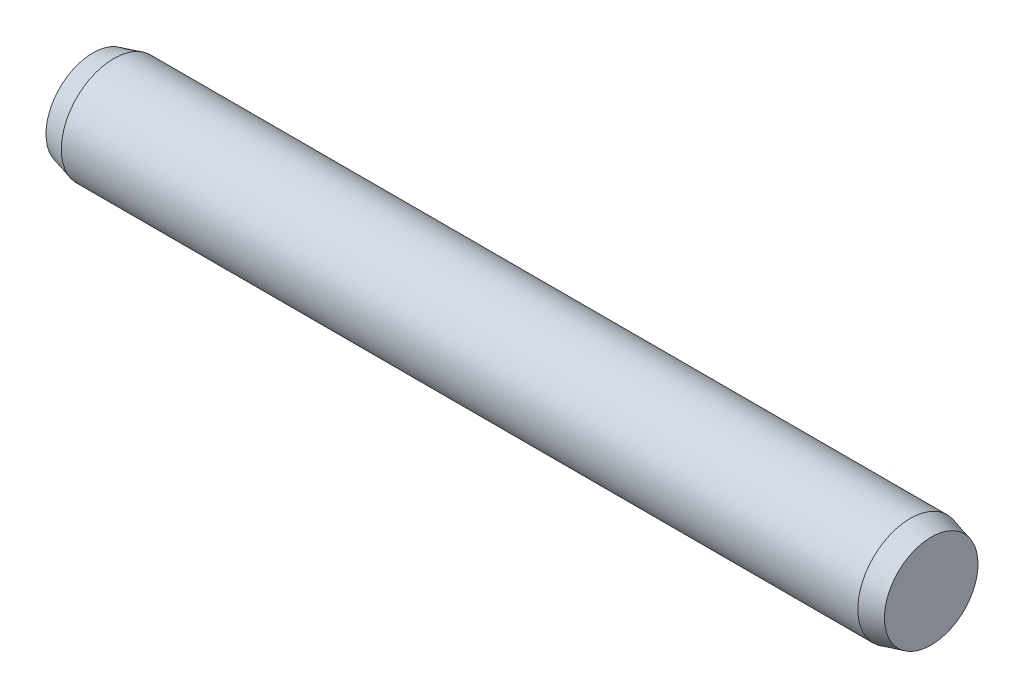
SolidWorks part; units mm, degrees
ref_plane "Front Plane" through (0, 0, 0) normal (0, 0, 1) x (1, 0, 0)
ref_plane "Top Plane" through (0, 0, 0) normal (0, 1, 0) x (1, 0, 0)
ref_plane "Right Plane" through (0, 0, 0) normal (1, 0, 0) x (0, 0, -1)
sketch "Sketch1" plane through (0, 0, 0) normal (0, 0, 1) x (1, 0, 0)
  line L0 (-5.7, 0) -> (5.7, 0) construction
  line L1 (5.7, 0.75) -> (5.7, -0.75) construction
  line L2 (-5.7, 0.75) -> (-5.7, -0.75) construction
  line L3 (6, 0.75) -> (6, -0.75) construction
  line L4 (-6, 0.75) -> (-6, -0.75) construction
  line L5 (-5.7, 0) -> (-6, 0) construction
  line L6 (5.7, 0) -> (6, 0) construction
  dimension "Dia" = 1.5
  dimension "C" = 0.3
  dimension "D1" = 0.3
  dimension "Length" = 12
sketch "Sketch2" plane through (0, 0, 0) normal (1, 0, 0) x (0, 0, -1)
  circle A0 centre (0, 0) radius 0.75
extrude "Extrude1" add sketch "Sketch2" against normal up to vertex (5.7 mm away) and the other way up to vertex (5.7 mm away) up to point (-5.7, 0.75, 0) other way up to point (5.7, 0.75, 0)
sketch "Sketch3" plane through (5.7, 0, 0) normal (1, 0, 0) x (0, 0, -1)
  circle A1 centre (0, 0) radius 0.75
  circle A2 centre (0, 0) radius 0.75
  dimension "D1" = 0
extrude "Extrude2" add sketch "Sketch3" along normal up to vertex (0.3 mm away) draft 15 up to point (6, 0, 0)
sketch "Sketch4" plane through (-5.7, 0, 0) normal (-1, 0, 0) x (0, 0, 1)
  circle A1 centre (0, 0) radius 0.75
  circle A2 centre (0, 0) radius 0.75
  dimension "D1" = 0
extrude "Extrude3" add sketch "Sketch4" along normal up to vertex (0.3 mm away) draft 15 up to point (-6, 0, 0)
equation "\"D1@Sketch1\" = \"C@Sketch1\""
